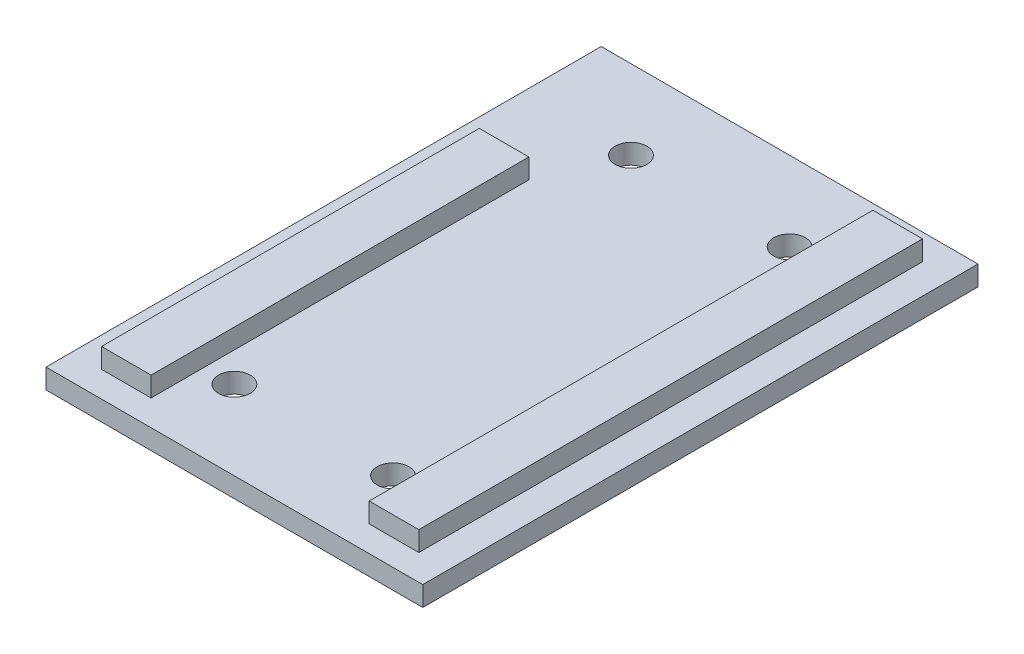
SolidWorks part; units mm, degrees
ref_plane "Front Plane" through (0, 0, 0) normal (0, 0, 1) x (1, 0, 0)
ref_plane "Top Plane" through (0, 0, 0) normal (0, 1, 0) x (1, 0, 0)
ref_plane "Right Plane" through (0, 0, 0) normal (1, 0, 0) x (0, 0, -1)
sketch "Sketch1" plane through (0, 0, 0) normal (0, 1, 0) x (1, 0, 0)
  line L1 (-19, 28) -> (19, 28)
  line L2 (-19, 28) -> (-19, -28)
  line L3 (-19, -28) -> (19, -28)
  line L4 (19, 28) -> (19, -28)
  line L5 (-19, 28) -> (19, -28) construction
  line L6 (-19, -28) -> (19, 28) construction
  point P0 (0, 0)
  dimension "D1" = 38
  dimension "D2" = 56
extrude "Boss-Extrude1" add sketch "Sketch1" along normal blind 2
sketch "Sketch2" plane through (0, 2, 0) normal (0, 1, 0) x (1, 0, 0)
  line L0 (16, 0) -> (19, 0) construction
  line L1 (-16, 12.7) -> (-11, 12.7)
  line L2 (-16, 12.7) -> (-16, -25.4)
  line L3 (-16, -25.4) -> (-11, -25.4)
  line L4 (-11, 12.7) -> (-11, -25.4)
  line L5 (16, -25.4) -> (11, -25.4)
  line L6 (16, -25.4) -> (16, 25.4)
  line L7 (16, 25.4) -> (11, 25.4)
  line L8 (11, -25.4) -> (11, 25.4)
  line L9 (19, -28) -> (19, 28) construction
  line L10 (-16, -6.35) -> (-19, -6.35) construction
  line L11 (-19, 28) -> (-19, -28) construction
  dimension "D1" = 5
  dimension "D2" = 3
  dimension "D3" = 50.8
  dimension "D4" = 38.1
extrude "Boss-Extrude2" add sketch "Sketch2" along normal blind 2
sketch "Sketch3" plane through (0, 4, 0) normal (0, 1, 0) x (1, 0, 0)
  line L0 (-14.77, -24.13) -> (-12.23, -24.13) construction
  line L1 (-15.02, -23.88) -> (-14.52, -23.88)
  line L2 (-15.02, -23.88) -> (-15.02, -24.38)
  line L3 (-15.02, -24.38) -> (-14.52, -24.38)
  line L4 (-14.52, -23.88) -> (-14.52, -24.38)
  line L5 (-15.02, -23.88) -> (-14.52, -24.38) construction
  line L6 (-15.02, -24.38) -> (-14.52, -23.88) construction
  line L7 (-12.48, -23.88) -> (-11.98, -23.88)
  line L8 (-12.48, -23.88) -> (-12.48, -24.38)
  line L9 (-12.48, -24.38) -> (-11.98, -24.38)
  line L10 (-11.98, -23.88) -> (-11.98, -24.38)
  line L11 (-12.48, -23.88) -> (-11.98, -24.38) construction
  line L12 (-12.48, -24.38) -> (-11.98, -23.88) construction
  line L13 (-13.5, -24.13) -> (-13.5, -25.4) construction
  line L14 (-16, -25.4) -> (-11, -25.4) construction
  point P0 (-14.77, -24.13)
  point P5 (-12.23, -24.13)
  dimension "D1" = 2.54
  dimension "D2" = 1.27
  dimension "D3" = 0.5
hole_wizard "Ø3.2 (3.2) Diameter Hole1" positions "Sketch6" profile "Sketch7" hole size "Ø3.2" standard "ISO" end condition through all
sketch "Sketch6" plane through (0, 2, 0) normal (0, 1, 0) x (1, 0, 0)
  line L0 (-8, -20) -> (-8, 20) construction
  line L1 (-8, 20) -> (8, 20) construction
  line L2 (8, 20) -> (8, -20) construction
  line L3 (8, -20) -> (-8, -20) construction
  line L5 (-8, 0) -> (0, 0) construction
  line L6 (0, 0) -> (0, 20) construction
  point P0 (-8, -20)
  point P2 (8, -20)
  point P4 (-8, 20)
  point P6 (8, 20)
  dimension "D1" = 40
  dimension "D2" = 16
sketch "Sketch7" plane through (-8, 2, 20) normal (1, 0, 0) x (0, 0, 1)
  line L0 (0, 0) -> (0, 2)
  line L1 (0, 2) -> (1.6, 2)
  line L2 (1.6, 2) -> (1.6, 0)
  line L5 (1.6, 0) -> (0, 0)
  line L11 (0, -6.35) -> (0, 107.95) construction
  dimension "Thru Hole Dia." = 3.2
  dimension "Thru Hole Depth" = 2
sketch "Sketch8" plane through (0, 0, -28) normal (0, 0, -1) x (-1, 0, 0)
  line L0 (0, 2) -> (0, 2.3) construction
  line L1 (-6.02, 12.9) -> (6.02, 12.9)
  line L2 (-6.02, 12.9) -> (-6.02, 2.3)
  line L3 (-6.02, 2.3) -> (6.02, 2.3)
  line L4 (6.02, 12.9) -> (6.02, 2.3)
  line L5 (-19, 2) -> (19, 2) construction
  dimension "D1" = 12.04
  dimension "D2" = 10.6
  dimension "D3" = 0.3
